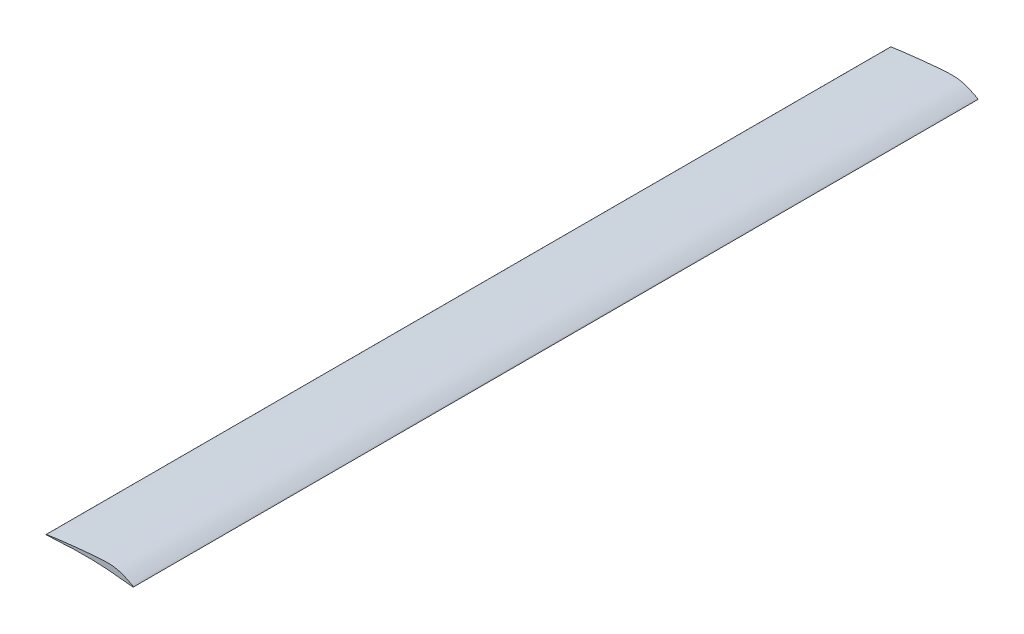
SolidWorks part; units mm, degrees
ref_plane "Front Plane" through (0, 0, 0) normal (0, 0, 1) x (1, 0, 0)
ref_plane "Top Plane" through (0, 0, 0) normal (0, 1, 0) x (1, 0, 0)
ref_plane "Right Plane" through (0, 0, 0) normal (1, 0, 0) x (0, 0, -1)
sketch "Sketch1" plane through (0, 0, 0) normal (0, 0, 1) x (1, 0, 0)
  line L0 (0, 0) -> (-2438.4, 0) construction
  spline S0 degree 3 poles (122.6288, -67.6169) (-355.6571, 198.4516) (-874.4993, 214.942) (-3054.9491, -49.7766) (-1650.6303, 48.1253) (-894.2332, 42.1772) (-485.5522, 3.196) (122.6288, -67.6169) (-355.6571, 198.4516) (-874.4993, 214.942) knots -0.211493 -0.047908 -0.015358 0 0.196797 0.488015 0.611703 0.788507 0.952092 0.984642 1 1.196797 1.488015 1.611703 only from (0, 0) to (0, 0)
  point P0 (65.2446, -41.9213)
  point P5 (-2457.6918, 3.703)
extrude "Boss-Extrude1" add sketch "Sketch1" along normal blind 24384
ref_plane "Plane1" through (-2438.4, 0, 0) normal (1, 0, 0) x (0, 0, -1)
